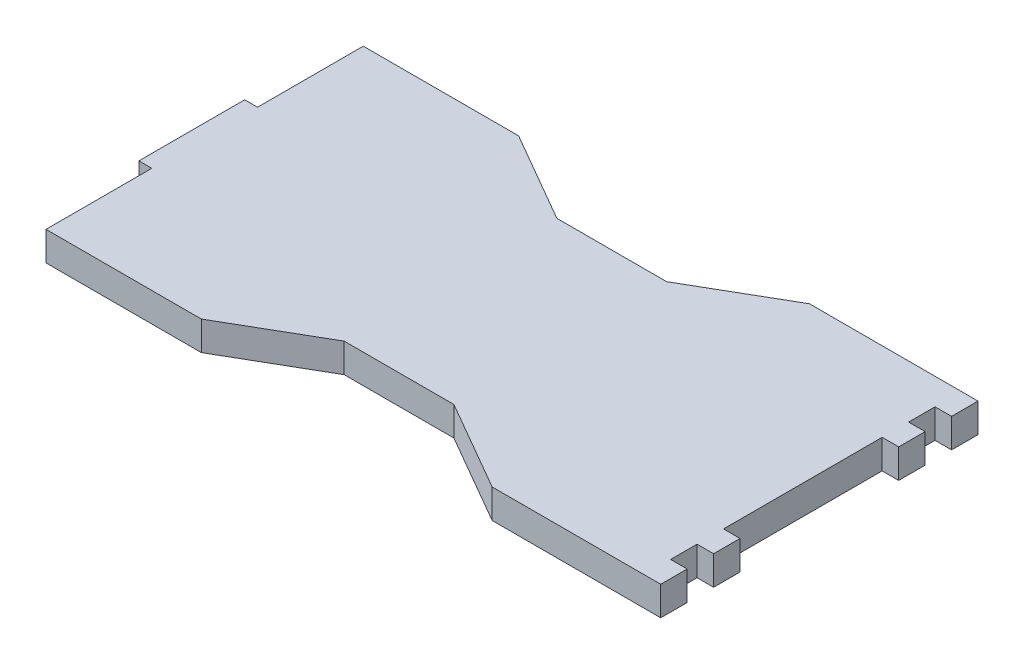
SolidWorks part; units mm, degrees
material "cardboard"
ref_plane "Front Plane" through (0, 0, 0) normal (0, 0, 1) x (1, 0, 0)
ref_plane "Top Plane" through (0, 0, 0) normal (0, 1, 0) x (1, 0, 0)
ref_plane "Right Plane" through (0, 0, 0) normal (1, 0, 0) x (0, 0, -1)
sketch "Sketch1" plane through (0, 0, 0) normal (0, 1, 0) x (1, 0, 0)
  line L0 (77.75, 11.3295) -> (70.8999, 7.3746)
  line L1 (103.25, -12.6705) -> (110.1001, -8.7155)
  line L2 (118.3999, 7.3746) -> (110.1001, 7.3746)
  line L3 (118.3999, -8.7155) -> (110.1001, -8.7155)
  line L4 (70.8999, 7.3746) -> (62.6001, 7.3746)
  line L5 (125.25, 11.3295) -> (118.3999, 7.3746)
  line L6 (125.25, -12.6705) -> (118.3999, -8.7155)
  line L7 (103.25, 11.3295) -> (110.1001, 7.3746)
  line L8 (125.25, 11.3295) -> (138, 11.3295)
  line L9 (125.25, -12.6705) -> (162, -12.6705)
  line L10 (55.75, 11.3295) -> (62.6001, 7.3746)
  line L11 (55.75, -12.6705) -> (62.6001, -8.7155)
  line L12 (77.75, -12.6705) -> (70.8999, -8.7155)
  line L13 (70.8999, -8.7155) -> (62.6001, -8.7155)
  line L14 (77.75, 11.3295) -> (103.25, 11.3295)
  line L15 (77.75, -12.6705) -> (103.25, -12.6705)
  line L16 (-12, 77.0795) -> (-8.0451, 70.2294)
  line L17 (12, 102.5795) -> (8.0451, 109.4297)
  line L18 (-8.0451, 117.7294) -> (-8.0451, 109.4297)
  line L19 (8.0451, 117.7294) -> (8.0451, 109.4297)
  line L20 (-8.0451, 70.2294) -> (-8.0451, 61.9297)
  line L21 (-12, 124.5795) -> (-8.0451, 117.7294)
  line L22 (12, 124.5795) -> (8.0451, 117.7294)
  line L23 (-12, 102.5795) -> (-8.0451, 109.4297)
  line L24 (-12, 124.5795) -> (-12, 137.3295)
  line L25 (12, 124.5795) -> (12, 161.3295)
  line L26 (-12, 55.0795) -> (-8.0451, 61.9297)
  line L27 (12, 55.0795) -> (8.0451, 61.9297)
  line L28 (12, 77.0795) -> (8.0451, 70.2294)
  line L29 (8.0451, 70.2294) -> (8.0451, 61.9297)
  line L30 (-12, 77.0795) -> (-12, 102.5795)
  line L31 (12, 77.0795) -> (12, 102.5795)
  line L32 (90.5, 36.3295) -> (90.5, 16.3295)
  line L33 (89.5, 36.3295) -> (89.5, 30.3295)
  line L34 (37, 11.3295) -> (43, 11.3295)
  line L35 (89.5, 30.3295) -> (91.5, 30.3295)
  line L36 (41.75, 11.3295) -> (41.75, 9.3295)
  line L37 (43, 11.3295) -> (55.75, 11.3295)
  line L38 (138, 11.3295) -> (138, -12.6705)
  line L39 (138, 11.3295) -> (162, 11.3295)
  line L40 (162, 11.3295) -> (162, 9.3295)
  line L41 (-28.4964, 13.6838) -> (0, -14.8126)
  line L42 (-28.4964, 13.6838) -> (-14.3543, 27.8259)
  line L43 (0, -14.8126) -> (14.1421, -0.6705)
  line L44 (-14.3543, 27.8259) -> (14.1421, -0.6705)
  line L45 (138, 11.3295) -> (138, 36.3295)
  line L46 (40, 36.3295) -> (162, 36.3295)
  line L47 (162, 36.3295) -> (162, 11.3295)
  line L48 (91.5, 30.3295) -> (91.5, 22.3295)
  line L49 (138, 36.3295) -> (138, 60.3295)
  line L50 (138, 60.3295) -> (147, 60.3295)
  line L51 (43, 36.3295) -> (43, 16.3295)
  line L52 (162, 60.3295) -> (162, 50.6515)
  line L53 (147, 60.3295) -> (147, 62.5295)
  line L54 (153, 62.5295) -> (153, 60.3295)
  line L55 (153, 60.3295) -> (162, 60.3295)
  line L56 (-59, 137.3295) -> (-59, 112.8295)
  line L57 (-39, 112.8295) -> (-39, 137.3295)
  line L58 (91.5, 22.3295) -> (89.5, 22.3295)
  line L59 (138, -12.6705) -> (138, -37.6705)
  line L60 (147, -37.6705) -> (153, -37.6705)
  line L61 (162, -37.6705) -> (162, -12.6705)
  line L62 (43, -37.6705) -> (43, -17.6705)
  line L63 (138, -37.6705) -> (138, -38.8505)
  line L64 (153, -38.8505) -> (162, -38.8505)
  line L65 (162, -38.8505) -> (162, -37.6705)
  line L66 (147, -38.8505) -> (147, -37.6705)
  line L67 (153, -38.8505) -> (153, -37.6705)
  line L68 (-38.18, -138.6705) -> (-38.18, -147.6705)
  line L69 (89.5, 22.3295) -> (89.5, 16.3295)
  line L70 (89.5, 11.3295) -> (89.5, 3.3295)
  line L71 (43, -12.6705) -> (55.75, -12.6705)
  line L72 (37, -12.6705) -> (43, -12.6705)
  line L73 (90.4738, 11.3295) -> (90.4738, -12.6705)
  line L74 (89.5, 3.3295) -> (91.5, 3.3295)
  line L75 (91.5, 3.3295) -> (91.5, -4.6705)
  line L76 (91.5, -4.6705) -> (89.5, -4.6705)
  line L77 (136, 11.3295) -> (136, 3.3295)
  line L78 (136, 3.3295) -> (140, 3.3295)
  line L79 (38.18, 161.3295) -> (38.18, 152.3295)
  line L80 (38, 34.3295) -> (38, 18.3295)
  line L81 (40, 16.3295) -> (138, 16.3295)
  line L82 (41.75, 23.3295) -> (41.75, 16.3295)
  line L83 (43, 29.3295) -> (40, 29.3295)
  line L84 (40, 29.3295) -> (40, 23.3295)
  line L85 (44.25, 5.3295) -> (41.75, 5.3295)
  line L86 (6, -42.4205) -> (6, -40.4205)
  line L87 (41.75, -6.6705) -> (44.25, -6.6705)
  line L88 (44.25, 5.3295) -> (44.25, -6.6705)
  line L89 (43, 11.3295) -> (43, 5.3295)
  line L90 (41.75, 9.3295) -> (44.25, 9.3295)
  line L91 (44.25, 9.3295) -> (44.25, 7.3295)
  line L92 (44.25, 7.3295) -> (41.75, 7.3295)
  line L93 (41.75, 7.3295) -> (41.75, 5.3295)
  line L94 (41.75, -8.6705) -> (41.75, -6.6705)
  line L95 (44.25, -8.6705) -> (41.75, -8.6705)
  line L96 (44.25, -10.6705) -> (44.25, -8.6705)
  line L97 (41.75, -10.6705) -> (44.25, -10.6705)
  line L98 (41.75, -12.6705) -> (41.75, -10.6705)
  line L99 (140, 3.3295) -> (140, -4.6705)
  line L100 (140, -4.6705) -> (136, -4.6705)
  line L101 (136, -4.6705) -> (136, -12.6705)
  line L102 (138, 13.3295) -> (146, 13.3295)
  line L103 (146, 13.3295) -> (146, 9.3295)
  line L104 (146, 9.3295) -> (154, 9.3295)
  line L105 (154, 9.3295) -> (154, 13.3295)
  line L106 (154, 13.3295) -> (162, 13.3295)
  line L107 (136.5, 36.3295) -> (136.5, 30.3295)
  line L108 (136.5, 30.3295) -> (139.5, 30.3295)
  line L109 (139.5, 30.3295) -> (139.5, 22.3295)
  line L110 (139.5, 22.3295) -> (136.5, 22.3295)
  line L111 (136.5, 22.3295) -> (136.5, 16.3295)
  line L112 (89.5, -4.6705) -> (89.5, -12.6705)
  line L113 (89.5, -23.6705) -> (89.5, -17.6705)
  line L114 (90.5, -37.6705) -> (90.5, -17.6705)
  line L115 (91.5, -23.6705) -> (89.5, -23.6705)
  line L116 (91.5, -31.6705) -> (91.5, -23.6705)
  line L117 (154, -14.6705) -> (162, -14.6705)
  line L118 (154, -10.6705) -> (154, -14.6705)
  line L119 (146, -10.6705) -> (154, -10.6705)
  line L120 (146, -14.6705) -> (146, -10.6705)
  line L121 (138, -14.6705) -> (146, -14.6705)
  line L122 (136.5, -23.6705) -> (136.5, -17.6705)
  line L123 (139.5, -23.6705) -> (136.5, -23.6705)
  line L124 (41.75, 36.3295) -> (41.75, 29.3295)
  line L125 (43, 23.3295) -> (40, 23.3295)
  line L126 (138, -37.6705) -> (40, -37.6705)
  line L127 (38, -35.6705) -> (38, -19.6705)
  line L128 (40, -17.6705) -> (138, -17.6705)
  line L129 (139.5, -31.6705) -> (139.5, -23.6705)
  line L130 (136.5, -31.6705) -> (139.5, -31.6705)
  line L131 (136.5, -37.6705) -> (136.5, -31.6705)
  line L132 (89.5, -31.6705) -> (91.5, -31.6705)
  line L133 (89.5, -37.6705) -> (89.5, -31.6705)
  line L134 (138, 38.3295) -> (146, 38.3295)
  line L135 (146, 38.3295) -> (146, 34.3295)
  line L136 (146, 34.3295) -> (154, 34.3295)
  line L137 (154, 34.3295) -> (154, 38.3295)
  line L138 (154, 38.3295) -> (162, 38.3295)
  line L139 (-44.5, 133.0795) -> (-44.5, 117.0795)
  line L140 (-56, 133.0795) -> (-53.5, 133.0795)
  line L141 (-56, 133.0795) -> (-56, 117.0795)
  line L142 (-56, 117.0795) -> (-53.5, 117.0795)
  line L143 (-53.5, 133.0795) -> (-53.5, 117.0795)
  line L144 (41.75, -24.6705) -> (41.75, -17.6705)
  line L145 (43, -24.6705) -> (40, -24.6705)
  line L146 (40, -30.6705) -> (40, -24.6705)
  line L147 (43, -30.6705) -> (40, -30.6705)
  line L148 (41.75, -37.6705) -> (41.75, -30.6705)
  line L149 (197, 4.3295) -> (197, -5.6705)
  line L150 (192, 9.3295) -> (162, 9.3295)
  line L151 (192, -10.6705) -> (162, -10.6705)
  line L152 (192, 9.3295) -> (197, 4.3295)
  line L153 (197, -5.6705) -> (192, -10.6705)
  line L154 (162, -10.6705) -> (162, -12.6705)
  line L155 (138, 62.5295) -> (147, 62.5295)
  line L156 (138, 62.5295) -> (138, 64.5295)
  line L157 (138, 64.5295) -> (162, 64.5295)
  line L158 (162, 64.5295) -> (162, 62.5295)
  line L159 (153, 62.5295) -> (162, 62.5295)
  line L160 (-42, 117.0795) -> (-44.5, 117.0795)
  line L161 (-42, 133.0795) -> (-42, 117.0795)
  line L162 (-42, 133.0795) -> (-44.5, 133.0795)
  line L163 (155.4, 50.6515) -> (162, 50.6515)
  line L164 (155.4, 50.6515) -> (155.4, 46.1515)
  line L165 (155.4, 46.1515) -> (162, 46.1515)
  line L166 (162, 46.1515) -> (162, 36.3295)
  line L167 (12, -78.4205) -> (8.0451, -71.5703)
  line L168 (-12, -103.9205) -> (-8.0451, -110.7706)
  line L169 (8.0451, -119.0703) -> (8.0451, -110.7706)
  line L170 (12, -37.6705) -> (12, -43.6705)
  line L171 (12, -42.4205) -> (10, -42.4205)
  line L172 (12, -43.6705) -> (12, -56.4205)
  line L173 (-8.0451, -119.0703) -> (-8.0451, -110.7706)
  line L174 (8.0451, -71.5703) -> (8.0451, -63.2706)
  line L175 (12, -125.9205) -> (8.0451, -119.0703)
  line L176 (-12, -125.9205) -> (-8.0451, -119.0703)
  line L177 (12, -103.9205) -> (8.0451, -110.7706)
  line L178 (12, -125.9205) -> (12, -138.6705)
  line L179 (-12, -125.9205) -> (-12, -162.6705)
  line L180 (12, -56.4205) -> (8.0451, -63.2706)
  line L181 (-12, -56.4205) -> (-8.0451, -63.2706)
  line L182 (37, -43.6705) -> (17, -43.6705)
  line L183 (-12, -78.4205) -> (-8.0451, -71.5703)
  line L184 (-8.0451, -71.5703) -> (-8.0451, -63.2706)
  line L185 (12, -78.4205) -> (12, -103.9205)
  line L186 (-12, -78.4205) -> (-12, -103.9205)
  line L187 (37, -91.1705) -> (17, -91.1705)
  line L188 (37, -90.1705) -> (31, -90.1705)
  line L189 (31, -90.1705) -> (31, -92.1705)
  line L190 (12, -138.6705) -> (-12, -138.6705)
  line L191 (12, -138.6705) -> (12, -162.6705)
  line L192 (12, -162.6705) -> (10, -162.6705)
  line L193 (12, -138.6705) -> (37, -138.6705)
  line L194 (37, -40.6705) -> (37, -162.6705)
  line L195 (-37, -43.6705) -> (-17, -43.6705)
  line L196 (37, -162.6705) -> (12, -162.6705)
  line L197 (31, -92.1705) -> (23, -92.1705)
  line L198 (37, -138.6705) -> (61, -138.6705)
  line L199 (61, -138.6705) -> (61, -147.6705)
  line L200 (61, -162.6705) -> (51.322, -162.6705)
  line L201 (61, -147.6705) -> (63.2, -147.6705)
  line L202 (63.2, -153.6705) -> (61, -153.6705)
  line L203 (61, -153.6705) -> (61, -162.6705)
  line L204 (-12, -43.6705) -> (-12, -56.4205)
  line L205 (-12, -37.6705) -> (-12, -43.6705)
  line L206 (23, -92.1705) -> (23, -90.1705)
  line L207 (-12, -138.6705) -> (-37, -138.6705)
  line L208 (-37, -147.6705) -> (-37, -153.6705)
  line L209 (38.18, 146.3295) -> (38.18, 137.3295)
  line L210 (35, -38.6705) -> (19, -38.6705)
  line L211 (17, -40.6705) -> (17, -138.6705)
  line L212 (24, -42.4205) -> (17, -42.4205)
  line L213 (30, -43.6705) -> (30, -40.6705)
  line L214 (30, -40.6705) -> (24, -40.6705)
  line L215 (6, -44.9205) -> (6, -42.4205)
  line L216 (-37, -162.6705) -> (-12, -162.6705)
  line L217 (-6, -42.4205) -> (-6, -44.9205)
  line L218 (6, -44.9205) -> (-6, -44.9205)
  line L219 (12, -43.6705) -> (6, -43.6705)
  line L220 (10, -42.4205) -> (10, -44.9205)
  line L221 (10, -44.9205) -> (8, -44.9205)
  line L222 (8, -44.9205) -> (8, -42.4205)
  line L223 (8, -42.4205) -> (6, -42.4205)
  line L224 (-8, -42.4205) -> (-6, -42.4205)
  line L225 (-8, -44.9205) -> (-8, -42.4205)
  line L226 (-10, -44.9205) -> (-8, -44.9205)
  line L227 (-10, -42.4205) -> (-10, -44.9205)
  line L228 (-12, -42.4205) -> (-10, -42.4205)
  line L229 (-37, -138.6705) -> (-38.18, -138.6705)
  line L230 (-38.18, -153.6705) -> (-38.18, -162.6705)
  line L231 (-38.18, -162.6705) -> (-37, -162.6705)
  line L232 (-38.18, -147.6705) -> (-37, -147.6705)
  line L233 (-38.18, -153.6705) -> (-37, -153.6705)
  line L234 (-162, 37.5095) -> (-153, 37.5095)
  line L235 (23, -90.1705) -> (17, -90.1705)
  line L236 (12, -90.1705) -> (4, -90.1705)
  line L237 (12, -91.1443) -> (-12, -91.1443)
  line L238 (4, -90.1705) -> (4, -92.1705)
  line L239 (4, -92.1705) -> (-4, -92.1705)
  line L240 (-4, -92.1705) -> (-4, -90.1705)
  line L241 (12, -136.6705) -> (4, -136.6705)
  line L242 (4, -136.6705) -> (4, -140.6705)
  line L243 (4, -140.6705) -> (-4, -140.6705)
  line L244 (-4, -140.6705) -> (-4, -136.6705)
  line L245 (-4, -136.6705) -> (-12, -136.6705)
  line L246 (14, -138.6705) -> (14, -146.6705)
  line L247 (14, -146.6705) -> (10, -146.6705)
  line L248 (10, -146.6705) -> (10, -154.6705)
  line L249 (10, -154.6705) -> (14, -154.6705)
  line L250 (14, -154.6705) -> (14, -162.6705)
  line L251 (37, -137.1705) -> (31, -137.1705)
  line L252 (31, -137.1705) -> (31, -140.1705)
  line L253 (31, -140.1705) -> (23, -140.1705)
  line L254 (37, -42.4205) -> (30, -42.4205)
  line L255 (24, -43.6705) -> (24, -40.6705)
  line L256 (-37, -138.6705) -> (-37, -40.6705)
  line L257 (-35, -38.6705) -> (-19, -38.6705)
  line L258 (-17, -40.6705) -> (-17, -138.6705)
  line L259 (23, -140.1705) -> (23, -137.1705)
  line L260 (23, -137.1705) -> (17, -137.1705)
  line L261 (-4, -90.1705) -> (-12, -90.1705)
  line L262 (-23, -90.1705) -> (-17, -90.1705)
  line L263 (-37, -91.1705) -> (-17, -91.1705)
  line L264 (-23, -92.1705) -> (-23, -90.1705)
  line L265 (-31, -92.1705) -> (-23, -92.1705)
  line L266 (-14, -154.6705) -> (-14, -162.6705)
  line L267 (-10, -154.6705) -> (-14, -154.6705)
  line L268 (-10, -146.6705) -> (-10, -154.6705)
  line L269 (-14, -146.6705) -> (-10, -146.6705)
  line L270 (-14, -138.6705) -> (-14, -146.6705)
  line L271 (-23, -137.1705) -> (-17, -137.1705)
  line L272 (-23, -140.1705) -> (-23, -137.1705)
  line L273 (-31, -140.1705) -> (-23, -140.1705)
  line L274 (-24, -42.4205) -> (-17, -42.4205)
  line L275 (-24, -43.6705) -> (-24, -40.6705)
  line L276 (-30, -40.6705) -> (-24, -40.6705)
  line L277 (-30, -43.6705) -> (-30, -40.6705)
  line L278 (-37, -42.4205) -> (-30, -42.4205)
  line L279 (-31, -137.1705) -> (-31, -140.1705)
  line L280 (-37, -137.1705) -> (-31, -137.1705)
  line L281 (-31, -90.1705) -> (-31, -92.1705)
  line L282 (-37, -90.1705) -> (-31, -90.1705)
  line L283 (39, -138.6705) -> (39, -146.6705)
  line L284 (39, -146.6705) -> (35, -146.6705)
  line L285 (35, -146.6705) -> (35, -154.6705)
  line L286 (35, -154.6705) -> (39, -154.6705)
  line L287 (39, -154.6705) -> (39, -162.6705)
  line L288 (5, -197.6705) -> (-5, -197.6705)
  line L289 (10, -192.6705) -> (10, -162.6705)
  line L290 (-10, -192.6705) -> (-10, -162.6705)
  line L291 (10, -192.6705) -> (5, -197.6705)
  line L292 (-5, -197.6705) -> (-10, -192.6705)
  line L293 (-10, -162.6705) -> (-12, -162.6705)
  line L294 (63.2, -138.6705) -> (63.2, -147.6705)
  line L295 (63.2, -138.6705) -> (65.2, -138.6705)
  line L296 (65.2, -138.6705) -> (65.2, -162.6705)
  line L297 (65.2, -162.6705) -> (63.2, -162.6705)
  line L298 (63.2, -153.6705) -> (63.2, -162.6705)
  line L299 (-37, -12.6705) -> (-43, -12.6705)
  line L300 (-41.75, -12.6705) -> (-41.75, -10.6705)
  line L301 (-43, -12.6705) -> (-55.75, -12.6705)
  line L302 (51.322, -156.0705) -> (51.322, -162.6705)
  line L303 (51.322, -156.0705) -> (46.822, -156.0705)
  line L304 (-43, -37.6705) -> (-43, -17.6705)
  line L305 (46.822, -156.0705) -> (46.822, -162.6705)
  line L306 (46.822, -162.6705) -> (37, -162.6705)
  line L307 (-77.75, -12.6705) -> (-70.8999, -8.7155)
  line L308 (-103.25, 11.3295) -> (-110.1001, 7.3746)
  line L309 (-118.3999, -8.7155) -> (-110.1001, -8.7155)
  line L310 (-118.3999, 7.3746) -> (-110.1001, 7.3746)
  line L311 (-70.8999, -8.7155) -> (-62.6001, -8.7155)
  line L312 (-125.25, -12.6705) -> (-118.3999, -8.7155)
  line L313 (-125.25, 11.3295) -> (-118.3999, 7.3746)
  line L314 (-103.25, -12.6705) -> (-110.1001, -8.7155)
  line L315 (-125.25, -12.6705) -> (-138, -12.6705)
  line L316 (-43, 36.3295) -> (-43, 16.3295)
  line L317 (-125.25, 11.3295) -> (-162, 11.3295)
  line L318 (-55.75, -12.6705) -> (-62.6001, -8.7155)
  line L319 (-55.75, 11.3295) -> (-62.6001, 7.3746)
  line L320 (-77.75, 11.3295) -> (-70.8999, 7.3746)
  line L321 (-70.8999, 7.3746) -> (-62.6001, 7.3746)
  line L322 (-77.75, -12.6705) -> (-103.25, -12.6705)
  line L323 (-77.75, 11.3295) -> (-103.25, 11.3295)
  line L324 (-90.5, -37.6705) -> (-90.5, -17.6705)
  line L325 (-43, 11.3295) -> (-55.75, 11.3295)
  line L326 (-37, 11.3295) -> (-43, 11.3295)
  line L327 (-89.5, -37.6705) -> (-89.5, -31.6705)
  line L328 (-89.5, -31.6705) -> (-91.5, -31.6705)
  line L329 (-138, -12.6705) -> (-138, 11.3295)
  line L330 (-138, -12.6705) -> (-162, -12.6705)
  line L331 (-162, -12.6705) -> (-162, -10.6705)
  line L332 (-138, -12.6705) -> (-138, -37.6705)
  line L333 (138, -38.8505) -> (147, -38.8505)
  line L334 (-38, -35.6705) -> (-38, -19.6705)
  line L335 (-40, -17.6705) -> (-138, -17.6705)
  line L336 (-41.75, -24.6705) -> (-41.75, -17.6705)
  line L337 (-43, -30.6705) -> (-40, -30.6705)
  line L338 (-40, -30.6705) -> (-40, -24.6705)
  line L339 (-44.25, -6.6705) -> (-41.75, -6.6705)
  line L340 (-40, -37.6705) -> (-162, -37.6705)
  line L341 (-41.75, 5.3295) -> (-44.25, 5.3295)
  line L342 (-44.25, -6.6705) -> (-44.25, 5.3295)
  line L343 (-43, -12.6705) -> (-43, -6.6705)
  line L344 (-41.75, -10.6705) -> (-44.25, -10.6705)
  line L345 (-44.25, -10.6705) -> (-44.25, -8.6705)
  line L346 (-44.25, -8.6705) -> (-41.75, -8.6705)
  line L347 (-41.75, -8.6705) -> (-41.75, -6.6705)
  line L348 (-41.75, 7.3295) -> (-41.75, 5.3295)
  line L349 (-44.25, 7.3295) -> (-41.75, 7.3295)
  line L350 (-44.25, 9.3295) -> (-44.25, 7.3295)
  line L351 (-41.75, 9.3295) -> (-44.25, 9.3295)
  line L352 (-41.75, 11.3295) -> (-41.75, 9.3295)
  line L353 (-162, -37.6705) -> (-162, -12.6705)
  line L354 (-91.5, -31.6705) -> (-91.5, -23.6705)
  line L355 (-138, -37.6705) -> (-138, -61.6705)
  line L356 (-138, -61.6705) -> (-147, -61.6705)
  line L357 (-162, -61.6705) -> (-162, -51.9925)
  line L358 (-147, -61.6705) -> (-147, -63.8705)
  line L359 (-153, -63.8705) -> (-153, -61.6705)
  line L360 (-153, -61.6705) -> (-162, -61.6705)
  line L361 (-91.5, -23.6705) -> (-89.5, -23.6705)
  line L362 (-138, 11.3295) -> (-138, 36.3295)
  line L363 (-147, 36.3295) -> (-153, 36.3295)
  line L364 (-162, 36.3295) -> (-162, 11.3295)
  line L365 (-138, 36.3295) -> (-138, 37.5095)
  line L366 (-162, 37.5095) -> (-162, 36.3295)
  line L367 (-147, 37.5095) -> (-147, 36.3295)
  line L368 (-153, 37.5095) -> (-153, 36.3295)
  line L369 (-147, 37.5095) -> (-138, 37.5095)
  line L370 (-89.5, -23.6705) -> (-89.5, -17.6705)
  line L371 (-89.5, -12.6705) -> (-89.5, -4.6705)
  line L372 (-90.4738, -12.6705) -> (-90.4738, 11.3295)
  line L373 (-89.5, -4.6705) -> (-91.5, -4.6705)
  line L374 (-41.75, -37.6705) -> (-41.75, -30.6705)
  line L375 (-43, -24.6705) -> (-40, -24.6705)
  line L376 (-138, 36.3295) -> (-40, 36.3295)
  line L377 (-38, 34.3295) -> (-38, 18.3295)
  line L378 (-40, 16.3295) -> (-138, 16.3295)
  line L379 (-91.5, -4.6705) -> (-91.5, 3.3295)
  line L380 (-91.5, 3.3295) -> (-89.5, 3.3295)
  line L381 (-136, -12.6705) -> (-136, -4.6705)
  line L382 (-136, -4.6705) -> (-140, -4.6705)
  line L383 (-140, -4.6705) -> (-140, 3.3295)
  line L384 (-140, 3.3295) -> (-136, 3.3295)
  line L385 (-136, 3.3295) -> (-136, 11.3295)
  line L386 (-138, -14.6705) -> (-146, -14.6705)
  line L387 (-146, -14.6705) -> (-146, -10.6705)
  line L388 (-146, -10.6705) -> (-154, -10.6705)
  line L389 (-154, -10.6705) -> (-154, -14.6705)
  line L390 (-154, -14.6705) -> (-162, -14.6705)
  line L391 (-136.5, -37.6705) -> (-136.5, -31.6705)
  line L392 (-37, 89.8295) -> (-17, 89.8295)
  line L393 (-37, 88.8295) -> (-31, 88.8295)
  line L394 (-41.75, 23.3295) -> (-41.75, 16.3295)
  line L395 (-43, 23.3295) -> (-40, 23.3295)
  line L396 (-40, 29.3295) -> (-40, 23.3295)
  line L397 (-43, 29.3295) -> (-40, 29.3295)
  line L398 (-41.75, 36.3295) -> (-41.75, 29.3295)
  line L399 (-136.5, -31.6705) -> (-139.5, -31.6705)
  line L400 (-139.5, -31.6705) -> (-139.5, -23.6705)
  line L401 (-139.5, -23.6705) -> (-136.5, -23.6705)
  line L402 (-136.5, -23.6705) -> (-136.5, -17.6705)
  line L403 (-89.5, 3.3295) -> (-89.5, 11.3295)
  line L404 (-89.5, 22.3295) -> (-89.5, 16.3295)
  line L405 (-90.5, 36.3295) -> (-90.5, 16.3295)
  line L406 (-91.5, 22.3295) -> (-89.5, 22.3295)
  line L407 (-91.5, 30.3295) -> (-91.5, 22.3295)
  line L408 (-154, 13.3295) -> (-162, 13.3295)
  line L409 (-154, 9.3295) -> (-154, 13.3295)
  line L410 (-146, 9.3295) -> (-154, 9.3295)
  line L411 (-146, 13.3295) -> (-146, 9.3295)
  line L412 (-138, 13.3295) -> (-146, 13.3295)
  line L413 (-136.5, 22.3295) -> (-136.5, 16.3295)
  line L414 (-139.5, 22.3295) -> (-136.5, 22.3295)
  line L415 (-139.5, 30.3295) -> (-139.5, 22.3295)
  line L416 (-136.5, 30.3295) -> (-139.5, 30.3295)
  line L417 (-136.5, 36.3295) -> (-136.5, 30.3295)
  line L418 (-89.5, 30.3295) -> (-91.5, 30.3295)
  line L419 (-89.5, 36.3295) -> (-89.5, 30.3295)
  line L420 (-138, -39.6705) -> (-146, -39.6705)
  line L421 (-146, -39.6705) -> (-146, -35.6705)
  line L422 (-146, -35.6705) -> (-154, -35.6705)
  line L423 (-154, -35.6705) -> (-154, -39.6705)
  line L424 (-154, -39.6705) -> (-162, -39.6705)
  line L425 (-12, 41.0795) -> (-10, 41.0795)
  line L426 (-31, 88.8295) -> (-31, 90.8295)
  line L427 (-12, 137.3295) -> (12, 137.3295)
  line L428 (-12, 137.3295) -> (-12, 161.3295)
  line L429 (-12, 161.3295) -> (-10, 161.3295)
  line L430 (-12, 137.3295) -> (-37, 137.3295)
  line L431 (-37, 137.3295) -> (-37, 161.3295)
  line L432 (-37, 161.3295) -> (-12, 161.3295)
  line L433 (-37, 137.3295) -> (-37, 42.3295)
  line L434 (-37, 42.3295) -> (-17, 42.3295)
  line L435 (-17, 42.3295) -> (-17, 137.3295)
  line L436 (-31, 90.8295) -> (-23, 90.8295)
  line L437 (-37, 137.3295) -> (-61, 137.3295)
  line L438 (-61, 137.3295) -> (-61, 146.3295)
  line L439 (-61, 161.3295) -> (-51.322, 161.3295)
  line L440 (-61, 146.3295) -> (-63.2, 146.3295)
  line L441 (-63.2, 152.3295) -> (-61, 152.3295)
  line L442 (-61, 152.3295) -> (-61, 161.3295)
  line L443 (-59, 112.8295) -> (-39, 112.8295)
  line L444 (37, 42.3295) -> (17, 42.3295)
  line L445 (-23, 90.8295) -> (-23, 88.8295)
  line L446 (37, 137.3295) -> (37, 42.3295)
  line L447 (17, 42.3295) -> (17, 137.3295)
  line L448 (12, 137.3295) -> (37, 137.3295)
  line L449 (37, 146.3295) -> (37, 152.3295)
  line L450 (37, 161.3295) -> (12, 161.3295)
  line L451 (12, 36.3295) -> (12, 55.0795)
  line L452 (37, 137.3295) -> (38.18, 137.3295)
  line L453 (38.18, 161.3295) -> (37, 161.3295)
  line L454 (38.18, 146.3295) -> (37, 146.3295)
  line L455 (38.18, 152.3295) -> (37, 152.3295)
  line L456 (-37, 42.3295) -> (-37, 39.3295)
  line L457 (-35, 37.3295) -> (-19, 37.3295)
  line L458 (-17, 39.3295) -> (-17, 42.3295)
  line L459 (35, 37.3295) -> (19, 37.3295)
  line L460 (17, 39.3295) -> (17, 42.3295)
  line L461 (-6, 43.5795) -> (-6, 41.0795)
  line L462 (-23, 88.8295) -> (-17, 88.8295)
  line L463 (6, 41.0795) -> (6, 43.5795)
  line L464 (-6, 43.5795) -> (6, 43.5795)
  line L465 (-12, 42.3295) -> (-6, 42.3295)
  line L466 (-10, 41.0795) -> (-10, 43.5795)
  line L467 (-10, 43.5795) -> (-8, 43.5795)
  line L468 (-8, 43.5795) -> (-8, 41.0795)
  line L469 (-8, 41.0795) -> (-6, 41.0795)
  line L470 (8, 41.0795) -> (6, 41.0795)
  line L471 (8, 43.5795) -> (8, 41.0795)
  line L472 (10, 43.5795) -> (8, 43.5795)
  line L473 (10, 41.0795) -> (10, 43.5795)
  line L474 (12, 41.0795) -> (10, 41.0795)
  line L475 (-12, 88.8295) -> (-4, 88.8295)
  line L476 (-12, 89.8033) -> (12, 89.8033)
  line L477 (-4, 88.8295) -> (-4, 90.8295)
  line L478 (-4, 90.8295) -> (4, 90.8295)
  line L479 (4, 90.8295) -> (4, 88.8295)
  line L480 (-12, 135.3295) -> (-4, 135.3295)
  line L481 (-4, 135.3295) -> (-4, 139.3295)
  line L482 (-4, 139.3295) -> (4, 139.3295)
  line L483 (4, 139.3295) -> (4, 135.3295)
  line L484 (4, 135.3295) -> (12, 135.3295)
  line L485 (-14, 137.3295) -> (-14, 145.3295)
  line L486 (-14, 145.3295) -> (-10, 145.3295)
  line L487 (-10, 145.3295) -> (-10, 153.3295)
  line L488 (-10, 153.3295) -> (-14, 153.3295)
  line L489 (-14, 153.3295) -> (-14, 161.3295)
  line L490 (-37, 135.8295) -> (-31, 135.8295)
  line L491 (-31, 135.8295) -> (-31, 138.8295)
  line L492 (-31, 138.8295) -> (-23, 138.8295)
  line L493 (-23, 138.8295) -> (-23, 135.8295)
  line L494 (-23, 135.8295) -> (-17, 135.8295)
  line L495 (4, 88.8295) -> (12, 88.8295)
  line L496 (23, 88.8295) -> (17, 88.8295)
  line L497 (37, 89.8295) -> (17, 89.8295)
  line L498 (23, 90.8295) -> (23, 88.8295)
  line L499 (31, 90.8295) -> (23, 90.8295)
  line L500 (-37, 41.0795) -> (-30, 41.0795)
  line L501 (30, 39.3295) -> (24, 39.3295)
  line L502 (24, 41.0795) -> (17, 41.0795)
  line L503 (-30, 42.3295) -> (-30, 39.3295)
  line L504 (-24, 41.0795) -> (-17, 41.0795)
  line L505 (14, 153.3295) -> (14, 161.3295)
  line L506 (10, 153.3295) -> (14, 153.3295)
  line L507 (10, 145.3295) -> (10, 153.3295)
  line L508 (14, 145.3295) -> (10, 145.3295)
  line L509 (14, 137.3295) -> (14, 145.3295)
  line L510 (23, 135.8295) -> (17, 135.8295)
  line L511 (23, 138.8295) -> (23, 135.8295)
  line L512 (31, 138.8295) -> (23, 138.8295)
  line L513 (31, 135.8295) -> (31, 138.8295)
  line L514 (37, 135.8295) -> (31, 135.8295)
  line L515 (31, 88.8295) -> (31, 90.8295)
  line L516 (37, 88.8295) -> (31, 88.8295)
  line L517 (12, 36.3295) -> (20.9645, 27.3651)
  line L518 (37, -12.6705) -> (28.0355, -21.6349)
  line L519 (-12, -37.6705) -> (-20.9645, -28.706)
  line L520 (24, 42.3295) -> (24, 39.3295)
  line L521 (-24, 42.3295) -> (-24, 39.3295)
  line L522 (30, 42.3295) -> (30, 39.3295)
  line L523 (37, 41.0795) -> (30, 41.0795)
  line L524 (-39, 137.3295) -> (-39, 145.3295)
  line L525 (-39, 145.3295) -> (-35, 145.3295)
  line L526 (-35, 145.3295) -> (-35, 153.3295)
  line L527 (-35, 153.3295) -> (-39, 153.3295)
  line L528 (-39, 153.3295) -> (-39, 161.3295)
  line L529 (-59, 135.8295) -> (-52, 135.8295)
  line L530 (-52, 135.8295) -> (-52, 138.8295)
  line L531 (-52, 138.8295) -> (-46, 138.8295)
  line L532 (-46, 138.8295) -> (-46, 135.8295)
  line L533 (-46, 135.8295) -> (-39, 135.8295)
  line L534 (-12, 36.3295) -> (-12, 55.0795)
  line L535 (43, -6.6705) -> (43, -12.6705)
  line L536 (6, 42.3295) -> (12, 42.3295)
  line L537 (-43, 5.3295) -> (-43, 11.3295)
  line L538 (-6, -43.6705) -> (-12, -43.6705)
  line L539 (-5, 196.3295) -> (5, 196.3295)
  line L540 (-10, 191.3295) -> (-10, 161.3295)
  line L541 (10, 191.3295) -> (10, 161.3295)
  line L542 (-10, 191.3295) -> (-5, 196.3295)
  line L543 (5, 196.3295) -> (10, 191.3295)
  line L544 (133.75, 55.3295) -> (117.75, 55.3295)
  line L545 (133.75, 55.3295) -> (133.75, 52.8295)
  line L546 (-197, -5.6705) -> (-197, 4.3295)
  line L547 (-192, -10.6705) -> (-162, -10.6705)
  line L548 (-192, 9.3295) -> (-162, 9.3295)
  line L549 (-192, -10.6705) -> (-197, -5.6705)
  line L550 (-197, 4.3295) -> (-192, 9.3295)
  line L551 (-162, 9.3295) -> (-162, 11.3295)
  line L552 (-138, -63.8705) -> (-147, -63.8705)
  line L553 (-138, -63.8705) -> (-138, -65.8705)
  line L554 (-138, -65.8705) -> (-162, -65.8705)
  line L555 (-162, -65.8705) -> (-162, -63.8705)
  line L556 (10, 161.3295) -> (12, 161.3295)
  line L557 (-153, -63.8705) -> (-162, -63.8705)
  line L558 (133.75, 52.8295) -> (117.75, 52.8295)
  line L559 (117.75, 55.3295) -> (117.75, 52.8295)
  line L560 (133.75, 43.8295) -> (117.75, 43.8295)
  line L561 (133.75, 41.3295) -> (133.75, 43.8295)
  line L562 (133.75, 41.3295) -> (117.75, 41.3295)
  line L563 (117.75, 41.3295) -> (117.75, 43.8295)
  line L564 (136.5, 58.3295) -> (136.5, 51.3295)
  line L565 (136.5, 51.3295) -> (139.5, 51.3295)
  line L566 (-155.4, -51.9925) -> (-162, -51.9925)
  line L567 (-155.4, -51.9925) -> (-155.4, -47.4925)
  line L568 (-155.4, -47.4925) -> (-162, -47.4925)
  line L569 (-63.2, 137.3295) -> (-63.2, 146.3295)
  line L570 (-63.2, 137.3295) -> (-65.2, 137.3295)
  line L571 (-65.2, 137.3295) -> (-65.2, 161.3295)
  line L572 (-65.2, 161.3295) -> (-63.2, 161.3295)
  line L573 (-63.2, 152.3295) -> (-63.2, 161.3295)
  line L574 (-162, -47.4925) -> (-162, -37.6705)
  line L575 (139.5, 51.3295) -> (139.5, 45.3295)
  line L576 (-46.3621, 123.1743) -> (-47.5, 123.1743)
  line L577 (-51.6379, 127.2156) -> (-50.5, 127.2156)
  line L578 (-51.6379, 127.2156) -> (-51.6379, 123.1743)
  line L579 (-51.6379, 123.1743) -> (-50.5, 123.1743)
  line L580 (-50.5, 127.2156) -> (-50.5, 123.1743)
  line L581 (-47.5, 127.2156) -> (-47.5, 123.1743)
  line L582 (-46.3621, 127.2156) -> (-47.5, 127.2156)
  line L583 (-46.3621, 127.2156) -> (-46.3621, 123.1743)
  line L584 (139.5, 45.3295) -> (136.5, 45.3295)
  line L585 (136.5, 45.3295) -> (136.5, 38.3295)
  line L586 (113.5, 38.3295) -> (138, 38.3295)
  line L587 (113.5, 58.3295) -> (113.5, 38.3295)
  line L588 (138, 58.3295) -> (113.5, 58.3295)
  line L589 (56, -134.4205) -> (56, -118.4205)
  line L590 (56, -134.4205) -> (53.5, -134.4205)
  line L591 (-51.322, 154.7295) -> (-51.322, 161.3295)
  line L592 (-51.322, 154.7295) -> (-46.822, 154.7295)
  line L593 (-46.822, 154.7295) -> (-46.822, 161.3295)
  line L594 (-46.822, 161.3295) -> (-37, 161.3295)
  line L595 (53.5, -134.4205) -> (53.5, -118.4205)
  line L596 (56, -118.4205) -> (53.5, -118.4205)
  line L597 (-13.8934, 34.4361) -> (-12, 36.3295)
  line L598 (-20.9645, 34.4361) -> (-23.0858, 36.5574)
  line L599 (-35.1066, 20.294) -> (-37.2279, 22.4153)
  line L600 (-37.2279, 22.4153) -> (-23.0858, 36.5574)
  line L601 (6, -40.4205) -> (-6, -40.4205)
  line L602 (41.75, 5.3295) -> (39.75, 5.3295)
  line L603 (-6, -42.4205) -> (-6, -40.4205)
  line L604 (41.75, -6.6705) -> (39.75, -6.6705)
  line L605 (39.75, 5.3295) -> (39.75, -6.6705)
  line L606 (-41.75, -6.6705) -> (-39.75, -6.6705)
  line L607 (-39.75, -6.6705) -> (-39.75, 5.3295)
  line L608 (-41.75, 5.3295) -> (-39.75, 5.3295)
  line L609 (-6, 41.0795) -> (-6, 39.0795)
  line L610 (-6, 39.0795) -> (6, 39.0795)
  line L611 (6, 41.0795) -> (6, 39.0795)
  line L612 (-37, 11.3295) -> (-35.1066, 13.2229)
  line L613 (-30, 39.3295) -> (-24, 39.3295)
  line L614 (25.9142, -19.5136) -> (18.8431, -26.5847)
  line L615 (18.8431, 25.2437) -> (25.9142, 18.1727)
  line L616 (25.9142, 18.1727) -> (28.0355, 20.294)
  line L617 (44.5, -134.4205) -> (44.5, -118.4205)
  line L618 (42, -134.4205) -> (44.5, -134.4205)
  line L619 (42, -134.4205) -> (42, -118.4205)
  line L620 (42, -118.4205) -> (44.5, -118.4205)
  line L621 (59, -137.1705) -> (52, -137.1705)
  line L622 (52, -137.1705) -> (52, -140.1705)
  line L623 (52, -140.1705) -> (46, -140.1705)
  line L624 (46, -140.1705) -> (46, -137.1705)
  line L625 (46, -137.1705) -> (39, -137.1705)
  line L626 (39, -114.1705) -> (39, -138.6705)
  line L627 (59, -114.1705) -> (39, -114.1705)
  line L628 (59, -138.6705) -> (59, -114.1705)
  line L629 (-133.75, -56.6705) -> (-117.75, -56.6705)
  line L630 (-133.75, -56.6705) -> (-133.75, -54.1705)
  line L631 (-133.75, -54.1705) -> (-117.75, -54.1705)
  line L632 (-117.75, -56.6705) -> (-117.75, -54.1705)
  line L633 (-133.75, -45.1705) -> (-117.75, -45.1705)
  line L634 (-133.75, -42.6705) -> (-133.75, -45.1705)
  line L635 (-133.75, -42.6705) -> (-117.75, -42.6705)
  line L636 (-117.75, -42.6705) -> (-117.75, -45.1705)
  line L637 (-136.5, -59.6705) -> (-136.5, -52.6705)
  line L638 (-136.5, -52.6705) -> (-139.5, -52.6705)
  line L639 (-139.5, -52.6705) -> (-139.5, -46.6705)
  line L640 (-139.5, -46.6705) -> (-136.5, -46.6705)
  line L641 (-136.5, -46.6705) -> (-136.5, -39.6705)
  line L642 (-113.5, -39.6705) -> (-138, -39.6705)
  line L643 (-113.5, -59.6705) -> (-113.5, -39.6705)
  line L644 (-138, -59.6705) -> (-113.5, -59.6705)
  line L645 (127.8861, 50.9675) -> (123.8448, 50.9675)
  line L646 (127.8861, 50.9675) -> (127.8861, 49.8295)
  line L647 (127.8861, 49.8295) -> (123.8448, 49.8295)
  line L648 (123.8448, 50.9675) -> (123.8448, 49.8295)
  line L649 (127.8861, 46.8295) -> (123.8448, 46.8295)
  line L650 (18.8431, 25.2437) -> (20.9645, 27.3651)
  line L651 (127.8861, 45.6916) -> (127.8861, 46.8295)
  line L652 (127.8861, 45.6916) -> (123.8448, 45.6916)
  line L653 (123.8448, 45.6916) -> (123.8448, 46.8295)
  line L654 (51.6379, -128.5566) -> (51.6379, -124.5153)
  line L655 (51.6379, -128.5566) -> (50.5, -128.5566)
  line L656 (50.5, -128.5566) -> (50.5, -124.5153)
  line L657 (51.6379, -124.5153) -> (50.5, -124.5153)
  line L658 (47.5, -128.5566) -> (47.5, -124.5153)
  line L659 (46.3621, -128.5566) -> (47.5, -128.5566)
  line L660 (46.3621, -128.5566) -> (46.3621, -124.5153)
  line L661 (46.3621, -124.5153) -> (47.5, -124.5153)
  line L662 (-127.8861, -52.3084) -> (-123.8448, -52.3084)
  line L663 (-127.8861, -52.3084) -> (-127.8861, -51.1705)
  line L664 (-127.8861, -51.1705) -> (-123.8448, -51.1705)
  line L665 (-123.8448, -52.3084) -> (-123.8448, -51.1705)
  line L666 (-127.8861, -48.1705) -> (-123.8448, -48.1705)
  line L667 (-127.8861, -47.0325) -> (-127.8861, -48.1705)
  line L668 (-127.8861, -47.0325) -> (-123.8448, -47.0325)
  line L669 (-123.8448, -47.0325) -> (-123.8448, -48.1705)
  line L670 (28.0355, 20.294) -> (37, 11.3295)
  line L671 (18.8431, -26.5847) -> (20.9645, -28.706)
  line L672 (25.9142, -19.5136) -> (28.0355, -21.6349)
  line L673 (-18.8431, -26.5847) -> (-25.9142, -19.5136)
  line L674 (-25.9142, -19.5136) -> (-28.0355, -21.6349)
  line L675 (-18.8431, -26.5847) -> (-20.9645, -28.706)
  line L676 (20.9645, -28.706) -> (12, -37.6705)
  line L677 (-28.0355, -21.6349) -> (-37, -12.6705)
  line L678 (37, 42.3295) -> (37, 39.3295)
  circle A0 centre (156.7175, 41.612) radius 1.5
  circle A1 centre (143.2825, 55.047) radius 1.5
  circle A2 centre (155.6569, 53.9864) radius 1.5
  circle A3 centre (144.3431, 42.6727) radius 1.5
  circle A4 centre (150, 48.3295) radius 3.1
  circle A5 centre (150, 23.8295) radius 5
  circle A6 centre (150, -25.1705) radius 5
  circle A7 centre (66.75, 26.3295) radius 5
  circle A8 centre (114.0006, 26.3295) radius 5
  circle A9 centre (66.75, -27.6705) radius 5
  circle A10 centre (114.0006, -27.6705) radius 5
  circle A11 centre (150, -0.6705) radius 7
  circle A12 centre (42.2825, -157.388) radius 1.5
  circle A13 centre (55.7175, -143.953) radius 1.5
  circle A14 centre (54.6569, -156.3273) radius 1.5
  circle A15 centre (43.3431, -145.0136) radius 1.5
  circle A16 centre (49, -150.6705) radius 3.1
  circle A17 centre (24.5, -150.6705) radius 5
  circle A18 centre (-42.2825, 156.047) radius 1.5
  circle A19 centre (-55.7175, 142.612) radius 1.5
  circle A20 centre (-54.6569, 154.9864) radius 1.5
  circle A21 centre (-43.3431, 143.6727) radius 1.5
  circle A22 centre (-49, 149.3295) radius 3.1
  circle A23 centre (-24.5, -150.6705) radius 5
  circle A24 centre (27, -67.4205) radius 5
  circle A25 centre (27, -114.6711) radius 5
  circle A26 centre (-27, -67.4205) radius 5
  circle A27 centre (-27, -114.6711) radius 5
  circle A28 centre (0, -150.6705) radius 7
  circle A29 centre (-156.7175, -42.953) radius 1.5
  circle A30 centre (-24.5, 149.3295) radius 5
  circle A31 centre (24.5, 149.3295) radius 5
  circle A32 centre (-143.2825, -56.388) radius 1.5
  circle A33 centre (-155.6569, -55.3273) radius 1.5
  circle A34 centre (-144.3431, -44.0136) radius 1.5
  circle A35 centre (-150, -49.6705) radius 3.1
  circle A36 centre (-150, -25.1705) radius 5
  circle A37 centre (-150, 23.8295) radius 5
  circle A38 centre (-66.75, -27.6705) radius 5
  circle A39 centre (-114.0006, -27.6705) radius 5
  circle A40 centre (-66.75, 26.3295) radius 5
  circle A41 centre (-114.0006, 26.3295) radius 5
  circle A42 centre (-150, -0.6705) radius 7
  circle A43 centre (-27, 66.0795) radius 5
  circle A44 centre (-27, 113.3301) radius 5
  circle A45 centre (27, 66.0795) radius 5
  circle A46 centre (27, 113.3301) radius 5
  arc A47 (40, 36.3295) -> (38, 34.3295) centre (40, 34.3295) ccw
  arc A48 (38, 18.3295) -> (40, 16.3295) centre (40, 18.3295) ccw
  arc A49 (-19, 37.3295) -> (-17, 39.3295) centre (-19, 39.3295) ccw
  arc A50 (-37, 39.3295) -> (-35, 37.3295) centre (-35, 39.3295) ccw
  arc A51 (37, 39.3295) -> (35, 37.3295) centre (35, 39.3295) cw
  arc A52 (19, 37.3295) -> (17, 39.3295) centre (19, 39.3295) cw
  arc A53 (40, -37.6705) -> (38, -35.6705) centre (40, -35.6705) cw
  arc A54 (38, -19.6705) -> (40, -17.6705) centre (40, -19.6705) cw
  arc A55 (37, -40.6705) -> (35, -38.6705) centre (35, -40.6705) ccw
  arc A56 (19, -38.6705) -> (17, -40.6705) centre (19, -40.6705) ccw
  arc A57 (-37, -40.6705) -> (-35, -38.6705) centre (-35, -40.6705) cw
  arc A58 (-19, -38.6705) -> (-17, -40.6705) centre (-19, -40.6705) cw
  arc A59 (-40, -37.6705) -> (-38, -35.6705) centre (-40, -35.6705) ccw
  arc A60 (-38, -19.6705) -> (-40, -17.6705) centre (-40, -19.6705) ccw
  arc A61 (-40, 36.3295) -> (-38, 34.3295) centre (-40, 34.3295) cw
  arc A62 (-38, 18.3295) -> (-40, 16.3295) centre (-40, 18.3295) cw
  arc A63 (-13.8934, 34.4361) -> (-20.9645, 34.4361) centre (-17.4289, 37.9717) cw
  arc A64 (-35.1066, 20.294) -> (-35.1066, 13.2229) centre (-38.6421, 16.7585) cw
  circle A65 centre (0, 149.3295) radius 7
  point P194 (0, -0.6705)
  point P589 (0, -0.6705)
  point P595 (0, -0.6705)
  point P596 (0, -0.6705)
  point P601 (0, -0.6705)
  point P604 (0, -0.6705)
  point P629 (0, -0.6705)
  point P660 (0, -0.6705)
  point P686 (0, -0.6705)
  point P715 (0, -0.6705)
  point P716 (0, -0.6705)
  point P740 (0, -0.6705)
  point P743 (0, -0.6705)
  point P783 (0, -0.6705)
  point P809 (0, -0.6705)
  point P816 (0, -0.6705)
  point P829 (0, -0.6705)
  point P860 (0, -0.6705)
  point P885 (0, -0.6705)
  point P890 (0, -0.6705)
  point P910 (0, -0.6705)
extrude "Boss-Extrude1" add sketch "Sketch1" along normal blind 2.2 contours L341 L537 L349 L350 L351 L325 L319 L321 L320 L323 L403 L380 L372 L373 L371 L322 L307 L311 L318 L301 L343 L344 L345 L346 L339 L342
